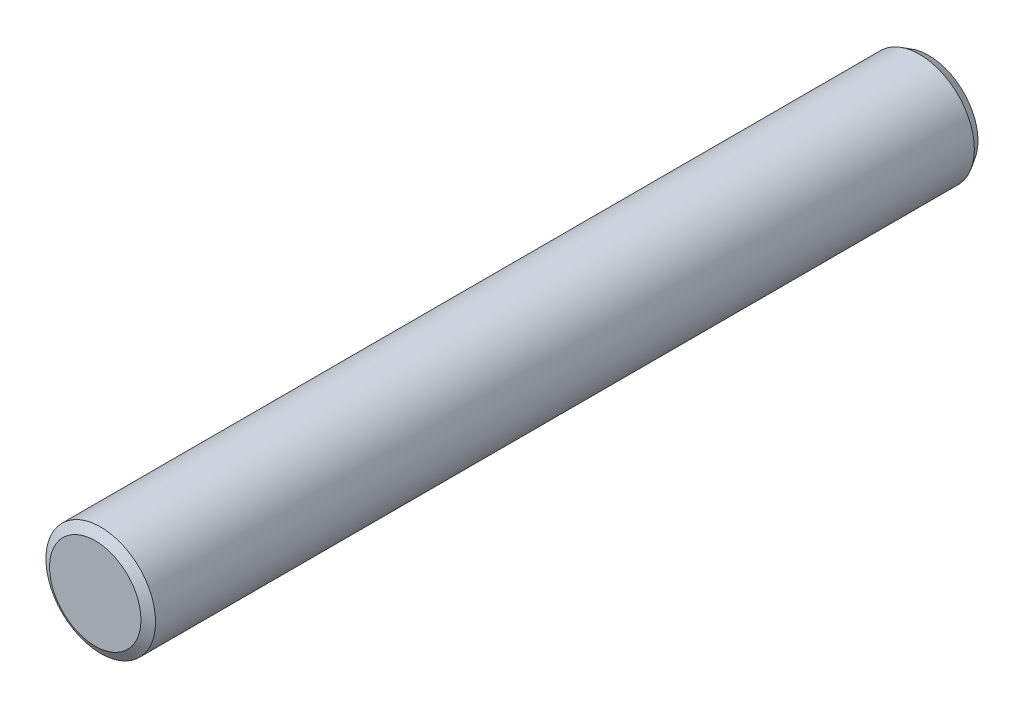
SolidWorks part; units mm, degrees
ref_plane "Front Plane" through (0, 0, 0) normal (0, 0, 1) x (1, 0, 0)
ref_plane "Top Plane" through (0, 0, 0) normal (0, 1, 0) x (1, 0, 0)
ref_plane "Right Plane" through (0, 0, 0) normal (1, 0, 0) x (0, 0, -1)
sketch "Sketch1" plane through (0, 0, 0) normal (0, 0, 1) x (1, 0, 0)
  circle A0 centre (0, 0) radius 5
extrude "Boss-Extrude1" add sketch "Sketch1" along normal blind 76
cosmetic thread "Cosmetic Thread1" parameters "D1"=32, "D2"=9.387
cosmetic thread "Cosmetic Thread2" parameters "D1"=18, "D2"=8.344
chamfer "Chamfer1" distance 0.5 angle 59 2 edges at (5, 0, 0) (5, 0, 76)
